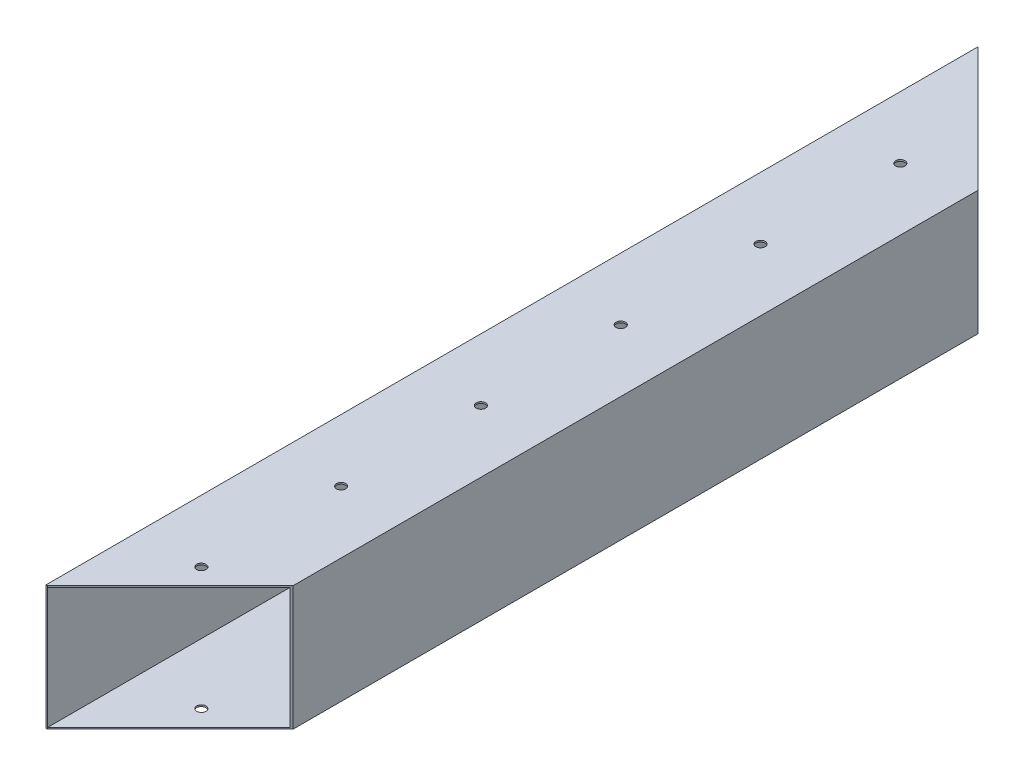
SolidWorks part; units mm, degrees
ref_plane "Alzado" through (0, 0, 0) normal (0, 0, 1) x (1, 0, 0)
ref_plane "Planta" through (0, 0, 0) normal (0, 1, 0) x (1, 0, 0)
ref_plane "Vista lateral" through (0, 0, 0) normal (1, 0, 0) x (0, 0, -1)
sketch "Croquis1" plane through (0, 0, 0) normal (0, 0, 1) x (1, 0, 0)
  line L1 (-20, 20) -> (20, 20)
  line L2 (-20, 20) -> (-20, -20)
  line L3 (-20, -20) -> (20, -20)
  line L4 (20, 20) -> (20, -20)
  line L5 (-20, 20) -> (20, -20) construction
  line L6 (-20, -20) -> (20, 20) construction
  line L7 (-19.5, 19.5) -> (19.5, 19.5)
  line L8 (-19.5, 19.5) -> (-19.5, -19.5)
  line L9 (-19.5, -19.5) -> (19.5, -19.5)
  line L10 (19.5, 19.5) -> (19.5, -19.5)
  line L11 (-19.5, 19.5) -> (19.5, -19.5) construction
  line L12 (-19.5, -19.5) -> (19.5, 19.5) construction
  point P0 (0, 0)
  point P6 (0, 0)
  dimension "D1" = 40
  dimension "D2" = 40
  dimension "D3" = 39
extrude "Saliente-Extruir2" add sketch "Croquis1" along normal blind 300
sketch "Croquis2" plane through (0, 20, 0) normal (0, 1, 0) x (1, 0, 0)
  line L0 (-19.5, -300) -> (20, -260.5)
  line L1 (20, -300) -> (20, 0) construction
  line L2 (-19.5, -300) -> (20, -300)
  line L3 (20, -300) -> (20, -260.5)
  dimension "D1" = 45
extrude "Cortar-Extruir1" cut sketch "Croquis2" against normal blind 300
sketch "Croquis3" plane through (0, -20, 0) normal (0, -1, 0) x (1, 0, 0)
  line L0 (-20, 0) -> (20, 40)
  line L1 (20, 260.5) -> (20, 0) construction
  line L2 (20, 40) -> (20, 0)
  line L3 (20, 0) -> (-20, 0)
  dimension "D1" = 45
extrude "Cortar-Extruir2" cut sketch "Croquis3" against normal blind 300 contours L3 L0 L2
sketch "Croquis4" plane through (0, -20, 0) normal (0, -1, 0) x (1, 0, 0)
  line L0 (0, 0) -> (0, 45) construction
  line L1 (0, 45) -> (0, 90) construction
  line L2 (0, 90) -> (0, 135) construction
  line L3 (0, 135) -> (0, 180) construction
  line L4 (0, 180) -> (0, 225) construction
  line L6 (0, 225) -> (0, 270) construction
  circle A0 centre (0, 45) radius 1.5
  circle A1 centre (0, 90) radius 1.5
  circle A2 centre (0, 135) radius 1.5
  circle A3 centre (0, 180) radius 1.5
  circle A4 centre (0, 225) radius 1.5
  circle A5 centre (0, 270) radius 1.5
  dimension "D2" = 3
  dimension "D4" = 3
  dimension "D6" = 3
  dimension "D8" = 3
  dimension "D10" = 3
  dimension "D12" = 3
  dimension "D1" = 45
  dimension "D3" = 45
  dimension "D5" = 45
  dimension "D7" = 45
  dimension "D9" = 45
  dimension "D11" = 45
extrude "Cortar-Extruir3" cut sketch "Croquis4" against normal blind 550
